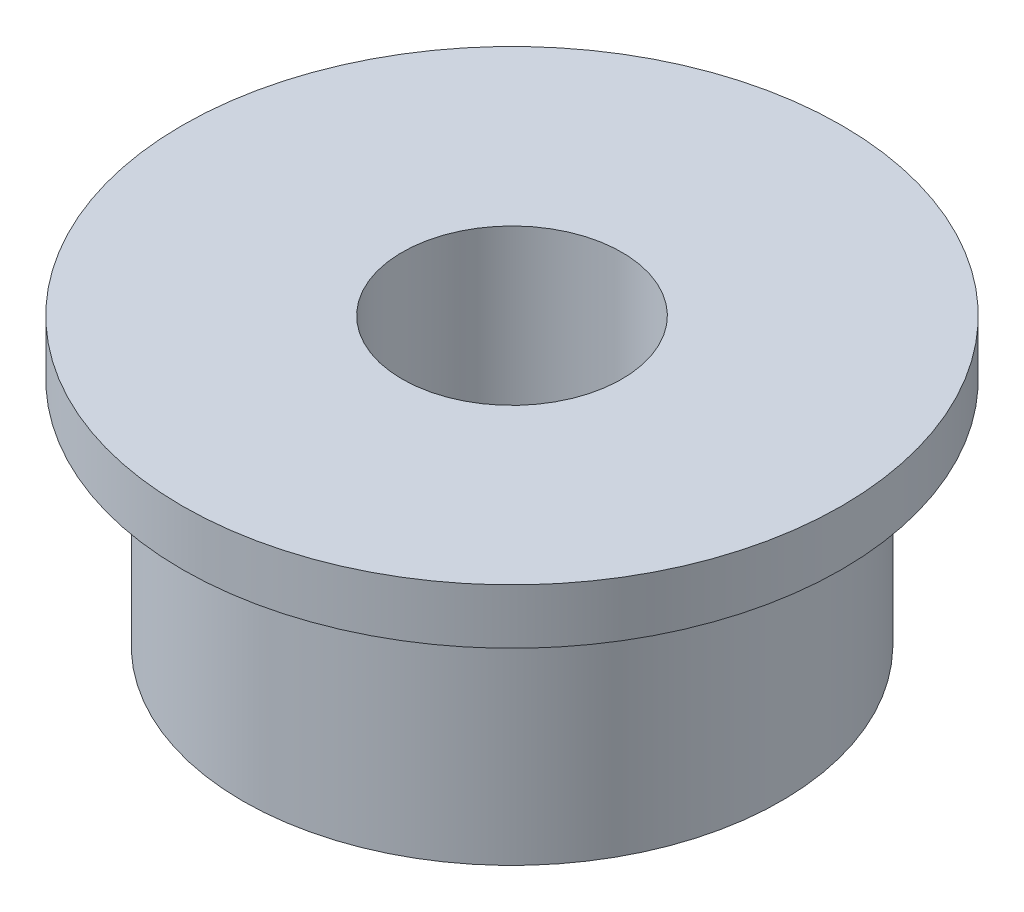
SolidWorks part; units mm, degrees
ref_plane "Front Plane" through (0, 0, 0) normal (0, 0, 1) x (1, 0, 0)
ref_plane "Top Plane" through (0, 0, 0) normal (0, 1, 0) x (1, 0, 0)
ref_plane "Right Plane" through (0, 0, 0) normal (1, 0, 0) x (0, 0, -1)
sketch "Sketch2" plane through (0, 0, 0) normal (1, 0, 0) x (0, 0, -1)
  line L0 (0, 22.4532) -> (0, -16.696) construction
  line L1 (-12.25, -6.5) -> (-12.25, 4)
  line L2 (-12.25, 4) -> (-15, 4)
  line L3 (-15, 4) -> (-15, 6.5)
  line L4 (-15, 6.5) -> (-5, 6.5)
  line L5 (-5, 6.5) -> (-5, -6.5)
  line L6 (-5, -6.5) -> (-12.25, -6.5)
  point P9 (-5, 0)
  dimension "D1" = 10
  dimension "D2" = 24.5
  dimension "D3" = 10
  dimension "D4" = 13
  dimension "D5" = 2.5
revolve "Revolve1" add sketch "Sketch2" angle 360 about L0
